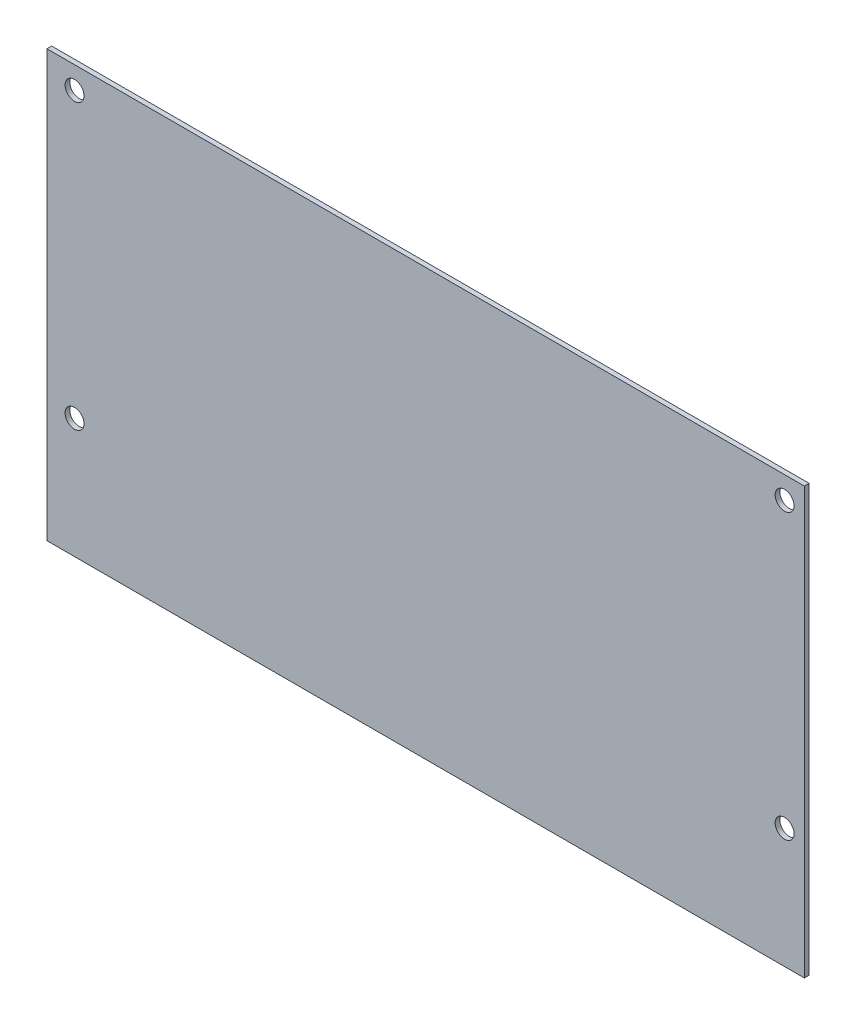
SolidWorks part; units mm, degrees
ref_plane "Piano frontale" through (0, 0, 0) normal (0, 0, 1) x (1, 0, 0)
ref_plane "Piano superiore" through (0, 0, 0) normal (0, 1, 0) x (1, 0, 0)
ref_plane "Piano destro" through (0, 0, 0) normal (1, 0, 0) x (0, 0, -1)
sketch "Schizzo1" plane through (0, 0, 0) normal (0, 0, 1) x (1, 0, 0)
  line L1 (0, 0) -> (160, 0)
  line L2 (0, 0) -> (0, 90)
  line L3 (0, 90) -> (160, 90)
  line L4 (160, 0) -> (160, 90)
  dimension "D1" = 90
  dimension "D2" = 160
extrude "Estrusione-Estrusione1" add sketch "Schizzo1" along normal blind 1
sketch "Schizzo3" plane through (0, 0, 1) normal (0, 0, 1) x (1, 0, 0)
  line L1 (5.8322, 85.3005) -> (155.8322, 85.3005)
  line L2 (5.8322, 85.3005) -> (5.8322, 25.3005)
  line L3 (5.8322, 25.3005) -> (155.8322, 25.3005)
  line L4 (155.8322, 85.3005) -> (155.8322, 25.3005)
  circle A0 centre (5.8322, 85.3005) radius 2
  circle A1 centre (155.8322, 85.3005) radius 2
  circle A2 centre (155.8322, 25.3005) radius 2
  circle A3 centre (5.8322, 25.3005) radius 2
  dimension "D1" = 4
  dimension "D2" = 150
  dimension "D3" = 60
extrude "Taglio-Estrusione1" cut sketch "Schizzo3" against normal blind 10 contours L1 A0 L2 | L2 A0 L1 | L4 A1 L1 | L1 A1 L4 | L3 A2 L4 | L4 A2 L3 | L3 A3 L2 | L2 A3 L3
sketch "Schizzo4" plane through (0, 0, 1) normal (0, 0, 1) x (1, 0, 0)
  text T0 "<b>Contributo degli amici di Trento</b>\r\n<b>       Claudio, Klaus, Gianni</b>\r\n<b>           Marco e Leonardo</b>" font "Century Gothic" height in points 32
